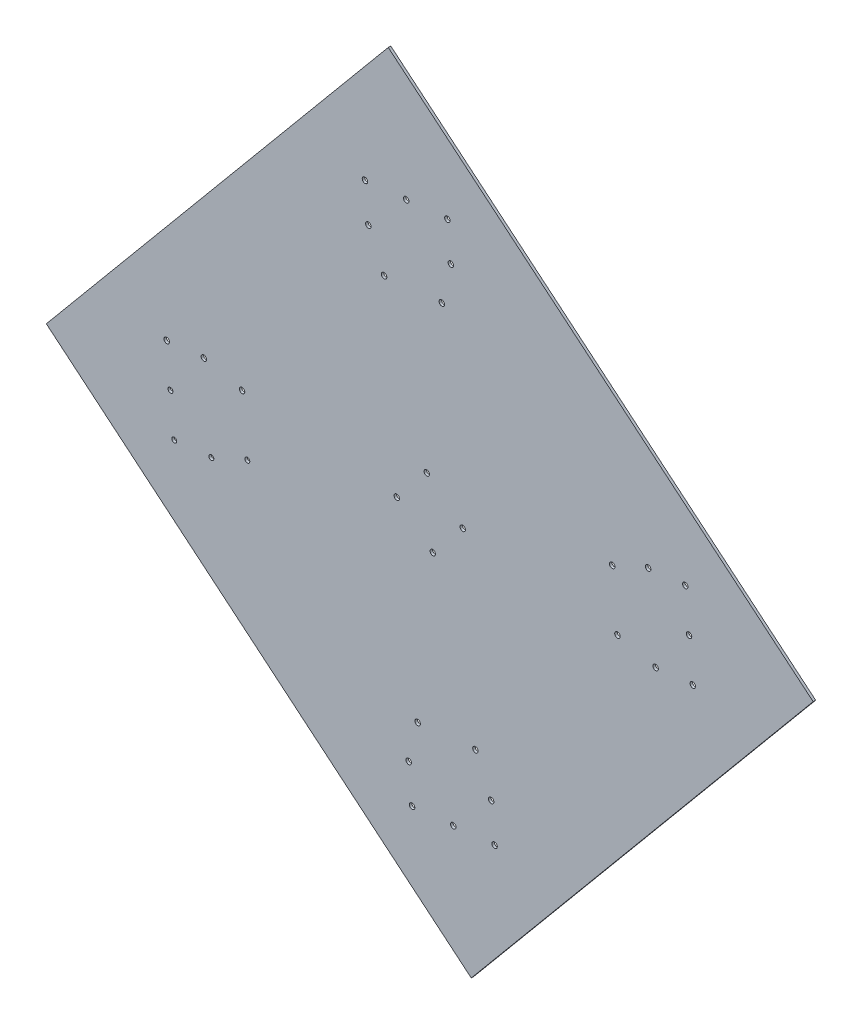
SolidWorks part; units mm, degrees
ref_plane "Front Plane" through (0, 0, 0) normal (0, 0, 1) x (1, 0, 0)
ref_plane "Top Plane" through (0, 0, 0) normal (0, 1, 0) x (1, 0, 0)
ref_plane "Right Plane" through (0, 0, 0) normal (1, 0, 0) x (0, 0, -1)
sketch "Sketch1" plane through (0, 0, 0) normal (0, 0, 1) x (1, 0, 0)
  line L4 (548.6161, -1807.1993) -> (967.9479, -1304.0235)
  line L5 (1061.7786, -2234.8537) -> (1481.1104, -1731.6779)
  line L74 (483.8308, -1746.7004) -> (1132.9659, -2287.6705)
  line L75 (1132.9659, -2287.6705) -> (1545.8957, -1792.1768)
  line L76 (1545.8957, -1792.1768) -> (896.7606, -1251.2067)
  line L77 (896.7606, -1251.2067) -> (483.8308, -1746.7004)
  line L78 (483.8308, -1746.7004) -> (1132.9659, -2287.6705)
  line L79 (1132.9659, -2287.6705) -> (1545.8957, -1792.1768)
  line L80 (1545.8957, -1792.1768) -> (896.7606, -1251.2067)
  line L81 (896.7606, -1251.2067) -> (483.8308, -1746.7004)
  dimension "D2" = 88.5
  dimension "D1" = 88.5
  dimension "D6" = 0
extrude "Boss-Extrude1" add sketch "Sketch1" along normal blind 3
sketch "Sketch2" plane through (0, 0, 3) normal (0, 0, 1) x (1, 0, 0)
  circle A1 centre (794.5523, -1824.6063) radius 3
  circle A2 centre (794.5523, -1824.6063) radius 3
  circle A3 centre (701.7538, -1797.8962) radius 3
  circle A4 centre (701.7538, -1797.8962) radius 3
  circle A5 centre (706.2795, -1847.6909) radius 3
  circle A6 centre (706.2795, -1847.6909) radius 3
  circle A7 centre (751.0948, -1843.6178) radius 3
  circle A8 centre (751.0948, -1843.6178) radius 3
  circle A9 centre (697.2281, -1748.1014) radius 3.3
  circle A10 centre (697.2281, -1748.1014) radius 3.3
  circle A11 centre (742.0434, -1744.0283) radius 3.3
  circle A12 centre (742.0434, -1744.0283) radius 3.3
  circle A13 centre (788.2164, -1754.8936) radius 3.3
  circle A14 centre (788.2164, -1754.8936) radius 3.3
  circle A15 centre (1054.699, -1765.818) radius 3.25
  circle A16 centre (1054.699, -1765.818) radius 3.25
  circle A17 centre (1011.2427, -1729.6028) radius 3.25
  circle A18 centre (1011.2427, -1729.6028) radius 3.25
  circle A19 centre (975.0274, -1773.0592) radius 3.25
  circle A20 centre (975.0274, -1773.0592) radius 3.25
  circle A21 centre (1018.4838, -1809.2744) radius 3.25
  circle A22 centre (1018.4838, -1809.2744) radius 3.25
  circle A23 centre (959.6956, -1549.1277) radius 3.3
  circle A24 centre (959.6956, -1549.1277) radius 3.3
  circle A25 centre (940.684, -1505.6701) radius 3.3
  circle A26 centre (940.684, -1505.6701) radius 3.3
  circle A27 centre (936.6109, -1460.8549) radius 3.3
  circle A28 centre (936.6109, -1460.8549) radius 3.3
  circle A29 centre (986.4057, -1456.3292) radius 3.3
  circle A30 centre (986.4057, -1456.3292) radius 3.3
  circle A31 centre (1036.2004, -1451.8035) radius 3.3
  circle A32 centre (1036.2004, -1451.8035) radius 3.3
  circle A33 centre (1040.2735, -1496.6187) radius 3.3
  circle A34 centre (1040.2735, -1496.6187) radius 3.3
  circle A35 centre (1029.4082, -1542.7917) radius 3.3
  circle A36 centre (1029.4082, -1542.7917) radius 3.3
  circle A37 centre (993.5261, -2087.0737) radius 3.3
  circle A38 centre (993.5261, -2087.0737) radius 3.3
  circle A39 centre (1043.3208, -2082.548) radius 3.3
  circle A40 centre (1043.3208, -2082.548) radius 3.3
  circle A41 centre (989.4529, -2042.2585) radius 3.3
  circle A42 centre (989.4529, -2042.2585) radius 3.3
  circle A43 centre (1000.3182, -1996.0855) radius 3.3
  circle A44 centre (1000.3182, -1996.0855) radius 3.3
  circle A45 centre (1070.0309, -1989.7495) radius 3.3
  circle A46 centre (1070.0309, -1989.7495) radius 3.3
  circle A47 centre (1089.0424, -2033.2071) radius 3.3
  circle A48 centre (1089.0424, -2033.2071) radius 3.3
  circle A49 centre (1093.1156, -2078.0224) radius 3.3
  circle A50 centre (1093.1156, -2078.0224) radius 3.3
  circle A51 centre (1241.5101, -1783.9836) radius 3.3
  circle A52 centre (1241.5101, -1783.9836) radius 3.3
  circle A53 centre (1287.6831, -1794.8489) radius 3.3
  circle A54 centre (1287.6831, -1794.8489) radius 3.3
  circle A55 centre (1332.4984, -1790.7758) radius 3.3
  circle A56 centre (1332.4984, -1790.7758) radius 3.3
  circle A57 centre (1327.9727, -1740.981) radius 3.3
  circle A58 centre (1327.9727, -1740.981) radius 3.3
  circle A59 centre (1323.447, -1691.1863) radius 3.3
  circle A60 centre (1323.447, -1691.1863) radius 3.3
  circle A61 centre (1278.6317, -1695.2594) radius 3.3
  circle A62 centre (1278.6317, -1695.2594) radius 3.3
  circle A63 centre (1235.1741, -1714.2709) radius 3.3
  circle A64 centre (1235.1741, -1714.2709) radius 3.3
  dimension "D1" = 0
  dimension "D2" = 0
  dimension "D3" = 0
  dimension "D4" = 0
  dimension "D5" = 0
  dimension "D6" = 0
  dimension "D7" = 0
  dimension "D8" = 0
  dimension "D9" = 0
  dimension "D10" = 0
  dimension "D11" = 0
  dimension "D12" = 0
  dimension "D13" = 0
  dimension "D14" = 0
  dimension "D15" = 0
  dimension "D16" = 0
  dimension "D17" = 0
  dimension "D18" = 0
  dimension "D19" = 0
  dimension "D20" = 0
  dimension "D21" = 0
  dimension "D22" = 0
  dimension "D23" = 0
  dimension "D24" = 0
  dimension "D25" = 0
  dimension "D26" = 0
  dimension "D27" = 0
  dimension "D28" = 0
  dimension "D29" = 0
  dimension "D30" = 0
  dimension "D31" = 0
  dimension "D32" = 0
extrude "Cut-Extrude1" cut sketch "Sketch2" against normal through all both and the other way through all
